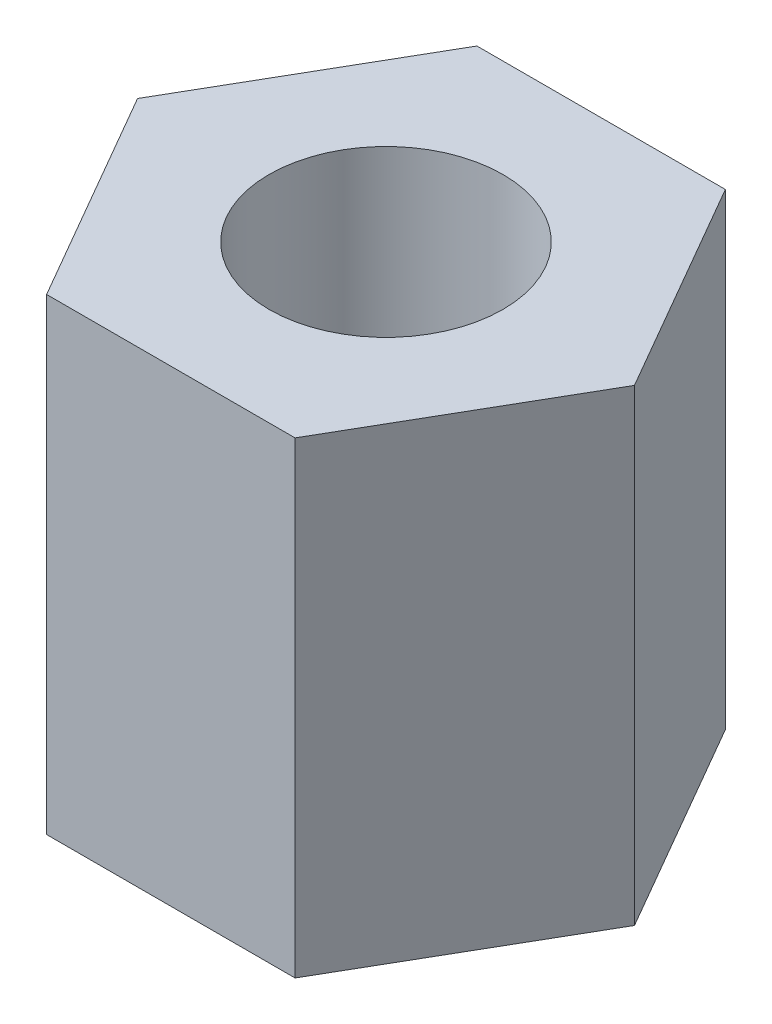
SolidWorks part; units mm, degrees
ref_plane "前视基准面" through (0, 0, 0) normal (0, 0, 1) x (1, 0, 0)
ref_plane "上视基准面" through (0, 0, 0) normal (0, 1, 0) x (1, 0, 0)
ref_plane "右视基准面" through (0, 0, 0) normal (1, 0, 0) x (0, 0, -1)
sketch "草图1" plane through (0, 0, 0) normal (0, 1, 0) x (1, 0, 0)
  line L1 (1.3279, -2.3) -> (2.6558, 0)
  line L2 (2.6558, 0) -> (1.3279, 2.3)
  line L3 (1.3279, 2.3) -> (-1.3279, 2.3)
  line L4 (-1.3279, 2.3) -> (-2.6558, 0)
  line L5 (-2.6558, 0) -> (-1.3279, -2.3)
  line L6 (-1.3279, -2.3) -> (1.3279, -2.3)
  circle A0 centre (0, 0) radius 2.3 construction
  dimension "D1" = 4.6
extrude "凸台-拉伸1" add sketch "草图1" along normal mid plane 5
hole_wizard "M3 螺纹孔1" positions "3D草图2" profile "草图3" tap size "M3" standard "GB" end condition up to next
sketch3d "3D草图2"
  point P0 (0, 0, 0)
  point P3 (0, 0, 0)
  point P5 (0, 2.5, 0)
sketch "草图3" plane through (0, 2.5, 0) normal (1, 0, 0) x (0, 0, 1)
  line L0 (0, 0) -> (0, 5.001)
  line L1 (0, 5.001) -> (1.25, 5.001)
  line L2 (1.25, 5.001) -> (1.25, 0)
  line L5 (1.25, 0) -> (0, 0)
  line L11 (0, -6.35) -> (0, 107.95) construction
  dimension "通孔螺纹孔钻头直径" = 2.5
  dimension "通孔螺纹孔钻头深度" = 5.001
cosmetic thread "孔螺蚊线1" parameters "D2"=3
cosmetic thread "孔螺蚊线2" parameters "D2"=3
cosmetic thread "孔螺蚊线3" parameters "D2"=3
